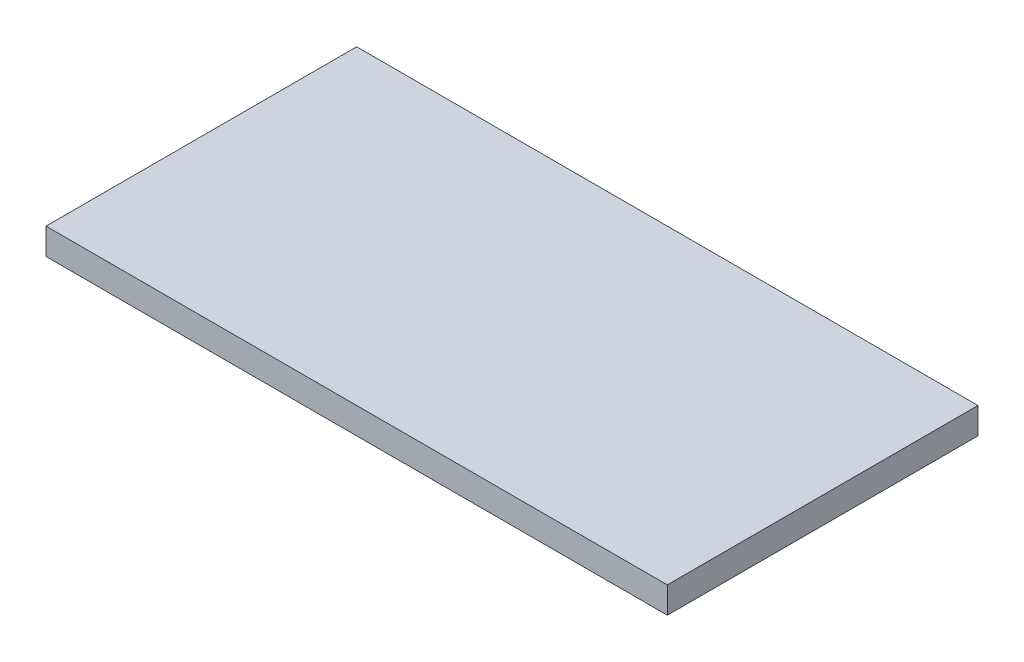
SolidWorks part; units mm, degrees
ref_plane "Front Plane" through (0, 0, 0) normal (0, 0, 1) x (1, 0, 0)
ref_plane "Top Plane" through (0, 0, 0) normal (0, 1, 0) x (1, 0, 0)
ref_plane "Right Plane" through (0, 0, 0) normal (1, 0, 0) x (0, 0, -1)
sketch "Sketch1" plane through (0, 0, 0) normal (0, 1, 0) x (1, 0, 0)
  line L1 (0, 0) -> (600, 0)
  line L2 (0, 0) -> (0, 300)
  line L3 (0, 300) -> (600, 300)
  line L4 (600, 0) -> (600, 300)
  dimension "D1" = 300
  dimension "D2" = 600
extrude "Boss-Extrude1" add sketch "Sketch1" along normal blind 25.4
